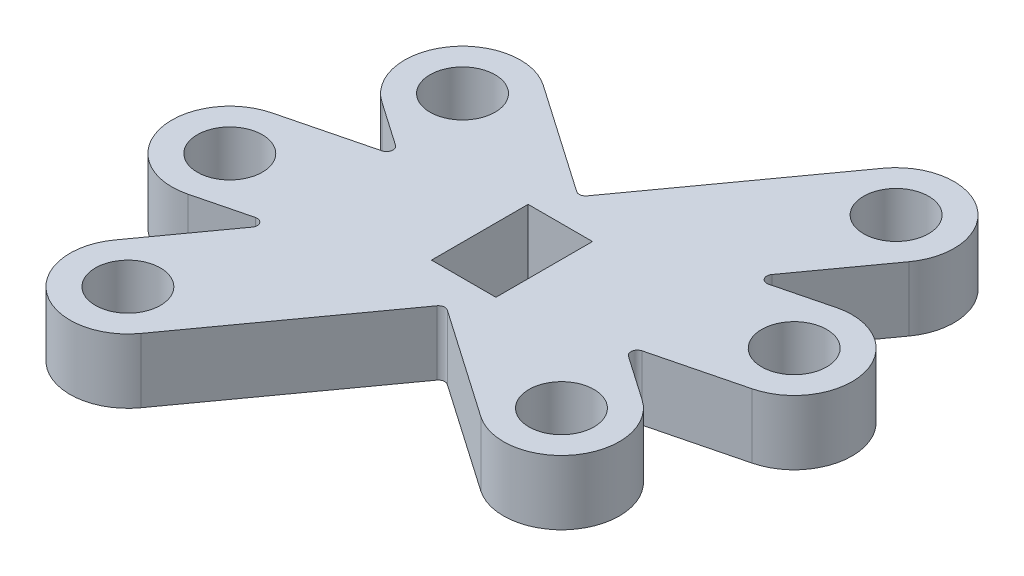
SolidWorks part; units mm, degrees
ref_plane "Front Plane" through (0, 0, 0) normal (0, 0, 1) x (1, 0, 0)
ref_plane "Top Plane" through (0, 0, 0) normal (0, 1, 0) x (1, 0, 0)
ref_plane "Right Plane" through (0, 0, 0) normal (1, 0, 0) x (0, 0, -1)
sketch "Sketch1" plane through (0, 0, 0) normal (0, 1, 0) x (1, 0, 0)
  line L0 (-35, -8.6603) -> (15, -43.3018) construction
  line L1 (-29.8745, -1.2624) -> (20.1255, -35.9039)
  line L2 (-40.1255, -16.0582) -> (9.8745, -50.6997)
  line L3 (15, 8.6603) -> (-35, -60.622) construction
  line L4 (22.298, 3.3935) -> (-27.702, -65.8888)
  line L5 (7.702, 13.9271) -> (-42.298, -55.3552)
  line L6 (25, -17.1635) -> (-45, -34.7985) construction
  line L7 (27.1987, -25.8908) -> (-42.8013, -43.5258)
  line L8 (22.8013, -8.4362) -> (-47.1987, -26.0712)
  line L9 (-15, -33.481) -> (-15, -18.481)
  line L10 (-15, -33.481) -> (-5, -33.481)
  line L11 (-15, -18.481) -> (-5, -18.481)
  line L12 (-5, -33.481) -> (-5, -18.481)
  line L13 (-15, -33.481) -> (-5, -18.481) construction
  line L14 (-15, -18.481) -> (-5, -33.481) construction
  circle A0 centre (-35, -8.6603) radius 5.05
  circle A1 centre (15, 8.6603) radius 5.05
  circle A2 centre (25, -17.1635) radius 5.05
  circle A3 centre (15, -43.3018) radius 5.05
  circle A4 centre (-35, -60.622) radius 5.05
  circle A5 centre (-45, -34.7985) radius 5.05
  arc A6 (-29.8745, -1.2624) -> (-40.1255, -16.0582) centre (-35, -8.6603) ccw
  arc A7 (9.8745, -50.6997) -> (20.1255, -35.9039) centre (15, -43.3018) ccw
  arc A8 (22.298, 3.3935) -> (7.702, 13.9271) centre (15, 8.6603) ccw
  arc A9 (-42.298, -55.3552) -> (-27.702, -65.8888) centre (-35, -60.622) ccw
  arc A10 (27.1987, -25.8908) -> (22.8013, -8.4362) centre (25, -17.1635) ccw
  arc A11 (-47.1987, -26.0712) -> (-42.8013, -43.5258) centre (-45, -34.7985) ccw
  point P0 (15, 8.6603)
  point P1 (25, -17.1635)
  point P2 (15, -43.3018)
  point P3 (-35, -60.622)
  point P4 (-45, -34.7985)
  point P5 (-35, -8.6603)
  point P19 (-10, -25.9811)
  point P26 (-10, -25.9809)
  point P33 (-10, -25.981)
  point P40 (0, 0)
  point P41 (0, 0)
  point P42 (0, 0)
  point P50 (-10, -25.981)
  dimension "D13" = 10.1
  dimension "D14" = 9
  dimension "D15" = 9
  dimension "D16" = 9
  dimension "D1" = 15
  dimension "D2" = 25
  dimension "D3" = 15
  dimension "D4" = 8.6603
  dimension "D5" = 43.3018
  dimension "D6" = 17.1635
  dimension "D7" = 35
  dimension "D8" = 35
  dimension "D9" = 45
  dimension "D10" = 34.7985
  dimension "D11" = 60.622
  dimension "D12" = 8.6603
  dimension "D17" = 10
  dimension "D18" = 15
extrude "Boss-Extrude1" add sketch "Sketch1" along normal blind 10 contours L12 L10 L2 L7 L4 L1 | L9 L11 L1 L8 L5 L2 | L8 L1 L5 | L4 L7 L2 | L10 L9 L2 L5 L7 | L5 L8 L2 | L7 L1 L4 | L12 L1 L4 L8 L11 | L4 A8 L5 L1 L8 A1 | L1 A6 L2 L8 L5 A0 | L7 A10 L8 L4 L1 A2 | L2 A7 L1 L7 L4 A3 | L5 A9 L4 L2 L7 A4 | L8 A11 L7 L5 L2 A5
fillet "Fillet1" radius 1 6 edges at (-31.752, 5, 40.7422) (-31.4132, 5, 22.0944) (-12.1316, 5, 13.5552) (11.7517, 5, 11.2199) (11.4131, 5, 29.8676) (-7.8686, 5, 38.4068)
equation "\"D15@Sketch1\"=\"D14@Sketch1\""
equation "\"D16@Sketch1\"=\"D14@Sketch1\""
